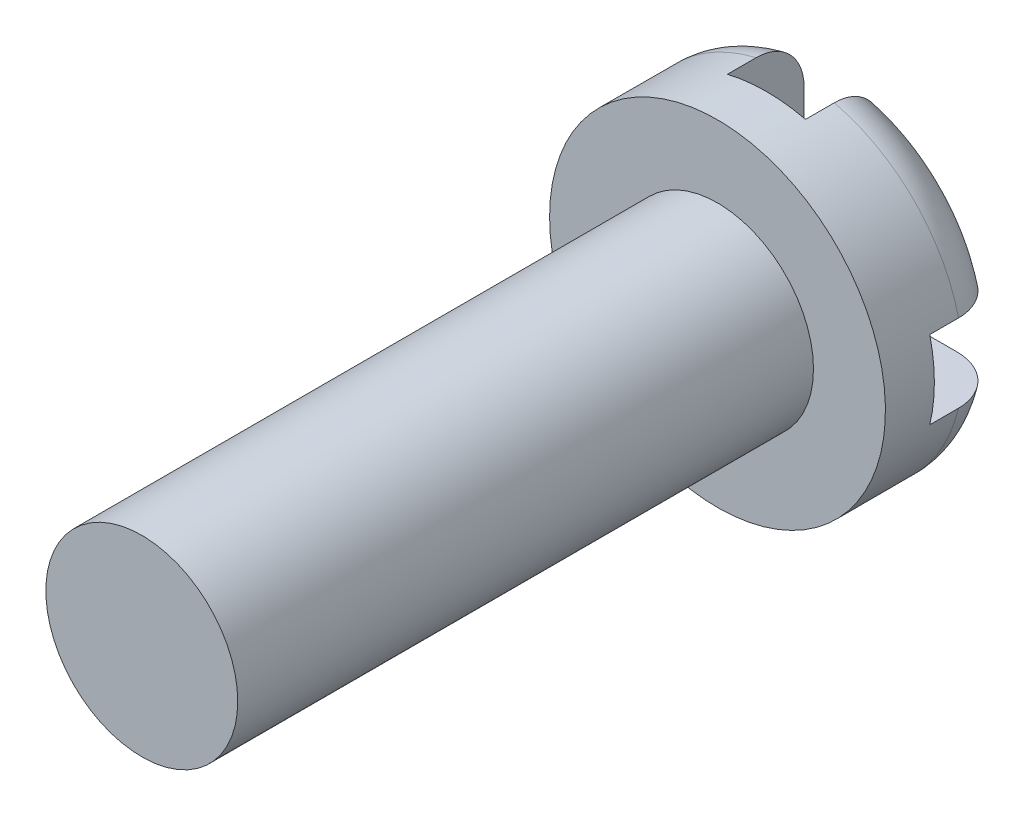
SolidWorks part; units mm, degrees
ref_plane "前视基准面" through (0, 0, 0) normal (0, 0, 1) x (1, 0, 0)
ref_plane "上视基准面" through (0, 0, 0) normal (0, 1, 0) x (1, 0, 0)
ref_plane "右视基准面" through (0, 0, 0) normal (1, 0, 0) x (0, 0, -1)
sketch "草图1" plane through (0, 0, 0) normal (0, 0, 1) x (1, 0, 0)
  circle A0 centre (0, 0) radius 1
extrude "凸台-拉伸1" add sketch "草图1" along normal blind 6
sketch "草图2" plane through (0, 0, 0) normal (0, 0, -1) x (-1, 0, 0)
  circle A0 centre (0, 0) radius 1.75
  dimension "D1" = 3.5
extrude "凸台-拉伸2" add sketch "草图2" along normal blind 1.31
fillet "圆角1" radius 0.5 1 edges at (-1.75, 0, -1.31)
sketch "草图3" plane through (0, 0, -1.31) normal (0, 0, -1) x (-1, 0, 0)
  line L0 (-0.7071, 0.7071) -> (-0.7071, 6.0064) construction
  line L1 (1, -1) -> (-1, -1) construction
  line L2 (1, -1) -> (1, 1) construction
  line L3 (1, 1) -> (-1, 1) construction
  line L4 (-1, -1) -> (-1, 1) construction
  line L5 (1, -1) -> (-1, 1) construction
  line L6 (1, 1) -> (-1, -1) construction
  line L7 (0.7071, 0.7071) -> (0.7071, 6.0064) construction
  line L8 (0.7071, 6.0064) -> (-0.7071, 6.0064) construction
  line L9 (0.7071, 0.7071) -> (6.0064, 0.7071) construction
  line L10 (0.7071, -0.7071) -> (6.0064, -0.7071) construction
  line L11 (6.0064, -0.7071) -> (6.0064, 0.7071) construction
  line L12 (0.7071, -0.7071) -> (0.7071, -6.0064) construction
  line L13 (-0.7071, -0.7071) -> (-0.7071, -6.0064) construction
  line L14 (-0.7071, -6.0064) -> (0.7071, -6.0064) construction
  line L15 (-0.7071, -0.7071) -> (-6.0064, -0.7071) construction
  line L16 (-0.7071, 0.7071) -> (-6.0064, 0.7071) construction
  line L17 (-6.0064, 0.7071) -> (-6.0064, -0.7071) construction
  line L18 (0.4071, 0.4071) -> (0.4071, 5.7064)
  line L19 (0.4071, 5.7064) -> (-0.4071, 5.7064)
  line L20 (-0.4071, 0.4071) -> (-0.4071, 5.7064)
  line L21 (-0.4071, 0.4071) -> (-5.7064, 0.4071)
  line L22 (-5.7064, 0.4071) -> (-5.7064, -0.4071)
  line L23 (-0.4071, -0.4071) -> (-5.7064, -0.4071)
  line L24 (-0.4071, -0.4071) -> (-0.4071, -5.7064)
  line L25 (-0.4071, -5.7064) -> (0.4071, -5.7064)
  line L26 (0.4071, -0.4071) -> (0.4071, -5.7064)
  line L27 (0.4071, -0.4071) -> (5.7064, -0.4071)
  line L28 (5.7064, -0.4071) -> (5.7064, 0.4071)
  line L29 (0.4071, 0.4071) -> (5.7064, 0.4071)
  circle A0 centre (0, 0) radius 1 construction
  dimension "D1" = 4
  dimension "D2" = 0.3
extrude "切除-拉伸1" cut sketch "草图3" against normal blind 0.8
sketch "草图4" plane through (0, 0, 0) normal (0, 0, 1) x (1, 0, 0)
  circle A0 centre (0, 0) radius 1.55
  dimension "D1" = 3.1
